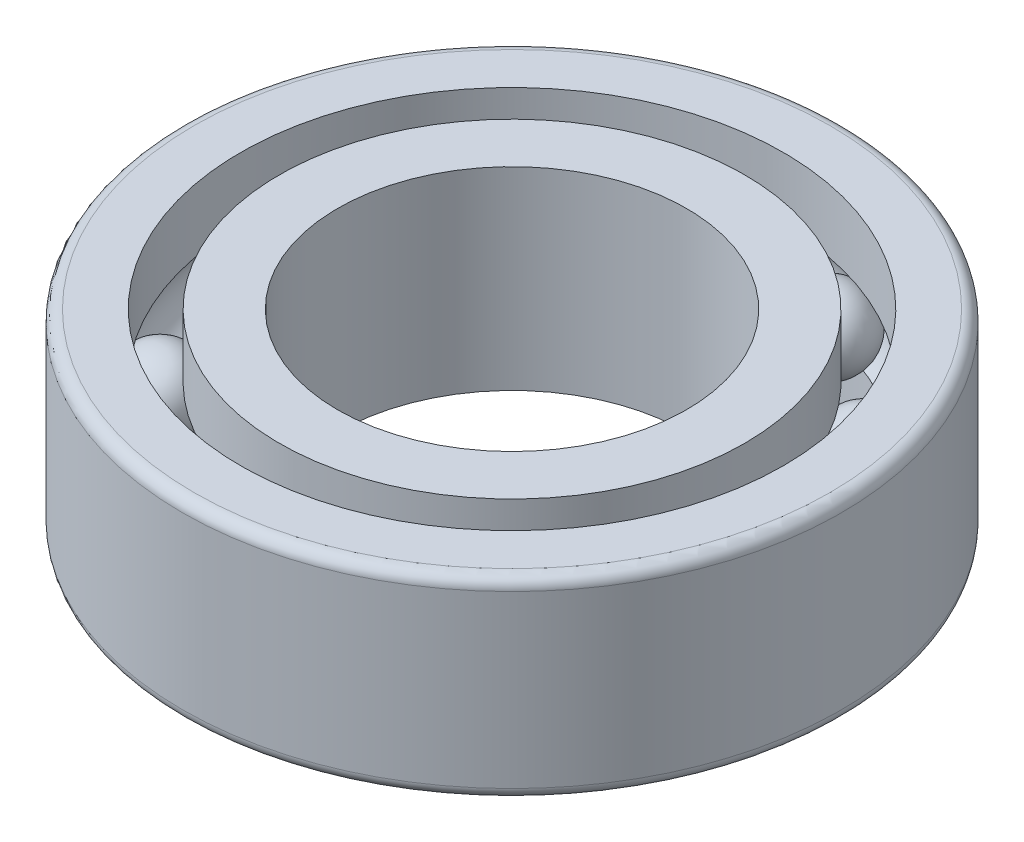
SolidWorks part; units mm, degrees
material "201 退火不锈钢 (SS)"
ref_plane "Front" through (0, 0, 0) normal (0, 0, 1) x (1, 0, 0)
ref_plane "Top" through (0, 0, 0) normal (0, 1, 0) x (1, 0, 0)
ref_plane "Right" through (0, 0, 0) normal (1, 0, 0) x (0, 0, -1)
sketch "草图1" plane through (0, 0, 0) normal (0, 1, 0) x (1, 0, 0)
  circle A0 centre (0, 0) radius 4.5
  circle A1 centre (0, 0) radius 8.5
  dimension "轴承内径" = 9
  dimension "轴承外径" = 17
extrude "凸台-拉伸1" add sketch "草图1" along normal mid plane 5
fillet "圆角1" radius 0.3 2 edges at (0, -2.5, 8.5) (0, 2.5, 8.5)
sketch "草图2" plane through (0, 0, 0) normal (0, 0, 1) x (1, 0, 0)
  line L0 (-1000, 0) -> (49000, 0) construction
  line L1 (0, -1000) -> (0, 49000) construction
  line L2 (-6.5, -999.4359) -> (-6.5, 49000.5641) construction
  line L5 (-8.5, 2.2) -> (-8.5, -2.2) construction
  line L6 (-4.5, 2.5) -> (-4.5, -2.5) construction
  line L12 (-6.5, 0) -> (-4.1351, 4.0962) construction
  line L13 (-6, 0.866) -> (-6, 2.5)
  line L16 (8.2, 2.5) -> (-8.2, 2.5) construction
  line L17 (-7, 0.866) -> (-7, 2.5)
  line L18 (-7, -0.866) -> (-7, -2.5)
  line L19 (-6, -0.866) -> (-6, -2.5)
  line L20 (-7, 2.5) -> (-6, 2.5)
  line L21 (-7, -2.5) -> (-6, -2.5)
  circle A2 centre (-6.5, 0) radius 1
  point P13 (-6, 0.866)
  dimension "滚珠直径" = 2
  dimension "接触角" = 60
revolve "切除-旋转1" cut sketch "草图2" angle 360 about L1
sketch "草图3" plane through (0, 0, 0) normal (0, 0, 1) x (1, 0, 0)
  line L0 (-6.5, -999.8949) -> (-6.5, 49000.1051) construction
  line L1 (-1000, 0) -> (49000, 0) construction
  line L4 (-6.5, -1) -> (-6.5, 1)
  line L5 (-8.5, 2.2) -> (-8.5, -2.2) construction
  line L6 (-4.5, 2.5) -> (-4.5, -2.5) construction
  arc A0 (-6.5, 1) -> (-6.5, -1) centre (-6.5, 0) ccw
  arc A2 (-7, 0.866) -> (-7, -0.866) centre (-6.5, 0) ccw construction
revolve "旋转1" add sketch "草图3" angle 360 about L0
pattern_circular "阵列(圆周)1" count 10 over 360 about axis through (0, 0, 0) along (0, 1, 0) of bodies 104
other "冻结***"
equation "\"滚珠数\"=12"
